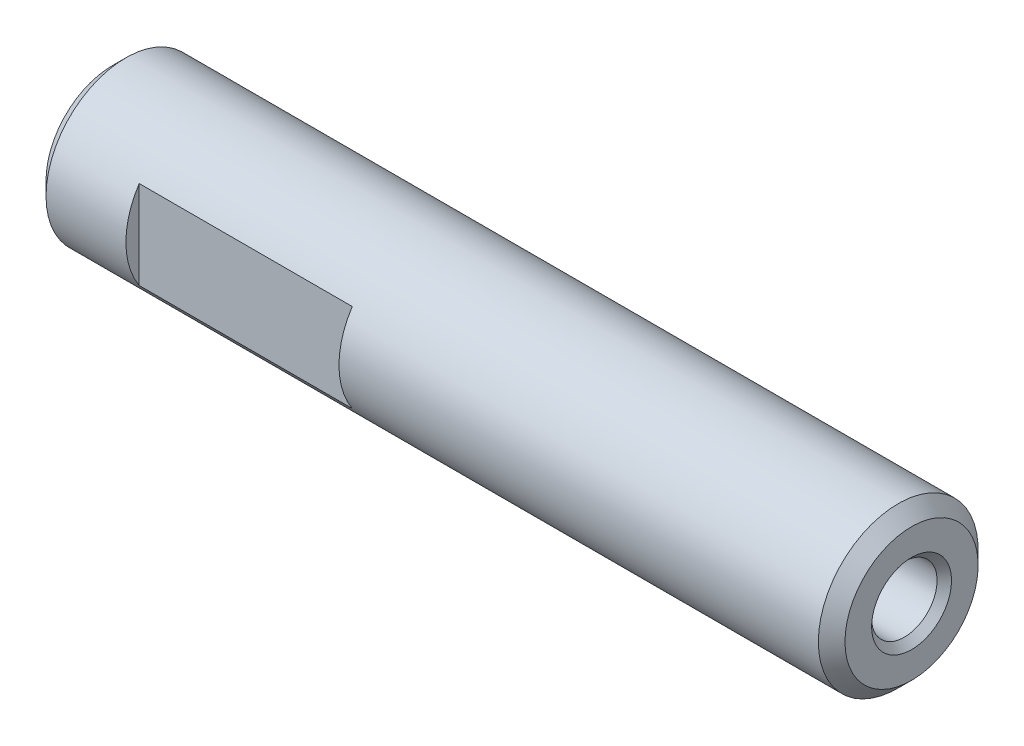
SolidWorks part; units mm, degrees
ref_plane "Front Plane" through (0, 0, 0) normal (0, 0, 1) x (1, 0, 0)
ref_plane "Top Plane" through (0, 0, 0) normal (0, 1, 0) x (1, 0, 0)
ref_plane "Right Plane" through (0, 0, 0) normal (1, 0, 0) x (0, 0, -1)
ref_plane "Plane1" through (0, 0, 0) normal (0, 0, 1) x (1, 0, 0)
sketch "Sketch1" plane through (0, 0, 0) normal (0, 0, 1) x (1, 0, 0)
  line L0 (0, 0) -> (0, 2.5)
  line L1 (0, 2.5) -> (0.5, 3)
  line L2 (0.5, 3) -> (29.5, 3)
  line L3 (29.5, 3) -> (30, 2.5)
  line L4 (30, 2.5) -> (30, 0)
  line L5 (30, 0) -> (0, 0)
  line L6 (30, 0) -> (0, 0) construction
revolve "Revolve1" add sketch "Sketch1" angle 360 about L6
ref_plane "Plane2" through (0, 0, 0) normal (0, 0, 1) x (1, 0, 0)
sketch "Sketch2" plane through (0, 0, 0) normal (0, 0, 1) x (1, 0, 0)
  line L0 (0, 0) -> (0, 1.5)
  line L1 (0, 1.5) -> (0.2705, 1.2295)
  line L2 (0.2705, 1.2295) -> (6.4901, 1.2295)
  line L3 (6.4901, 1.2295) -> (7.2, 0)
  line L4 (7.2, 0) -> (0, 0)
  line L5 (7.2, 0) -> (0, 0) construction
revolve "Cut-Revolve1" cut sketch "Sketch2" angle 360 about L5
ref_plane "Plane3" through (0, 0, 0) normal (0, 0, 1) x (1, 0, 0)
sketch "Sketch3" plane through (0, 0, 0) normal (0, 0, 1) x (1, 0, 0)
  line L0 (22.8, 0) -> (23.5099, 1.2295)
  line L1 (23.5099, 1.2295) -> (29.7295, 1.2295)
  line L2 (29.7295, 1.2295) -> (30, 1.5)
  line L3 (30, 1.5) -> (30, 0)
  line L4 (30, 0) -> (22.8, 0)
  line L5 (30, 0) -> (22.8, 0) construction
revolve "Cut-Revolve2" cut sketch "Sketch3" angle 360 about L5
ref_plane "Plane4" through (3.5, 0, 0) normal (1, 0, 0) x (0, 0, -1)
sketch "Sketch4" plane through (3.5, 0, 0) normal (1, 0, 0) x (0, 0, -1)
  line L0 (-5, 12) -> (-5, -12)
  line L1 (-5, -12) -> (5, -12)
  line L2 (5, -12) -> (5, 12)
  line L3 (5, 12) -> (-5, 12)
  line L4 (-2.5, 6) -> (-2.5, -6)
  line L5 (-2.5, -6) -> (2.5, -6)
  line L6 (2.5, -6) -> (2.5, 6)
  line L7 (2.5, 6) -> (-2.5, 6)
extrude "Cut-Extrude1" cut sketch "Sketch4" along normal blind 8
